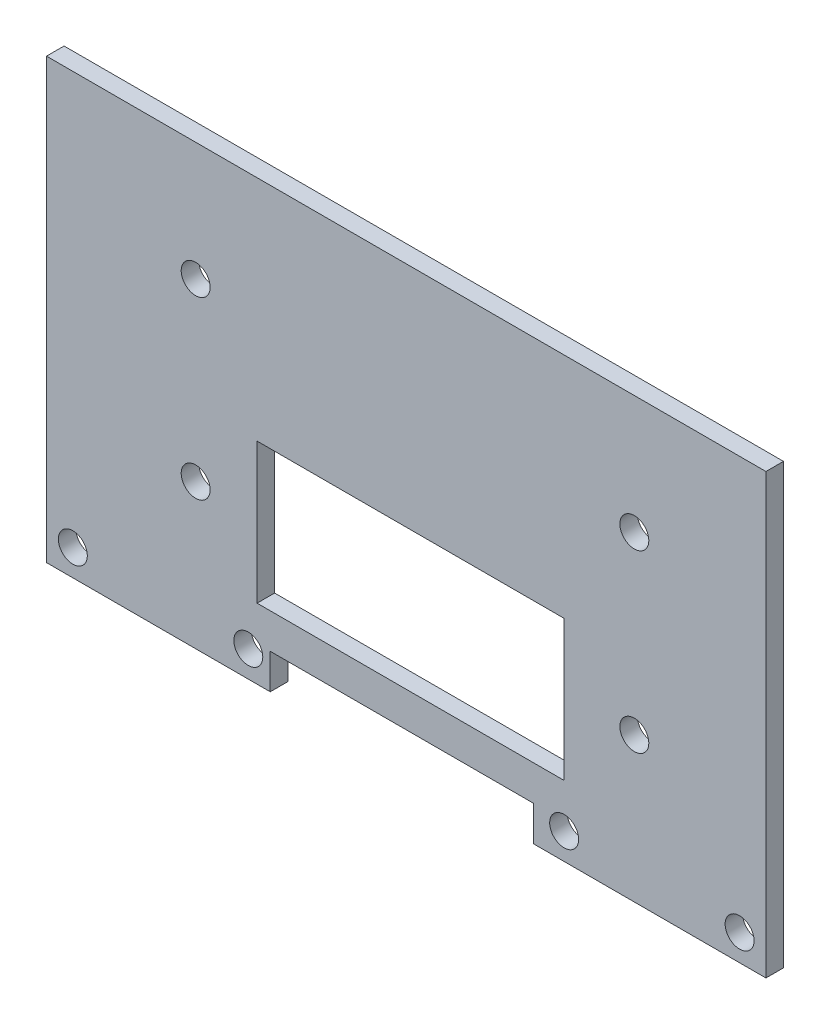
SolidWorks part; units mm, degrees
material "环氧板"
ref_plane "前视基准面" through (0, 0, 0) normal (0, 0, 1) x (1, 0, 0)
ref_plane "上视基准面" through (0, 0, 0) normal (0, 1, 0) x (1, 0, 0)
ref_plane "右视基准面" through (0, 0, 0) normal (1, 0, 0) x (0, 0, -1)
other "Configuration Table"
sketch "草图1" plane through (0, 0, 0) normal (0, 0, 1) x (1, 0, 0)
  line L1 (-40, 25) -> (40, 25)
  line L2 (-40, 25) -> (-40, -25)
  line L3 (-40, -25) -> (40, -25)
  line L4 (40, 25) -> (40, -25)
  line L5 (-40, 25) -> (40, -25) construction
  line L6 (-40, -25) -> (40, 25) construction
  point P0 (0, 0)
  dimension "D1" = 50
  dimension "D2" = 80
extrude "凸台-拉伸1" add sketch "草图1" along normal blind 2
sketch "草图5" plane through (0, 0, 2) normal (0, 0, 1) x (1, 0, 0)
  line L1 (-40, 25) -> (-42, 25)
  line L2 (-40, 25) -> (-40, -25)
  line L3 (-40, -25) -> (-42, -25)
  line L4 (-42, 25) -> (-42, -25)
  dimension "D1" = 2
extrude "凸台-拉伸2" add sketch "草图5" against normal blind 2
sketch "草图2" plane through (0, 0, 2) normal (0, 0, 1) x (1, 0, 0)
  line L0 (-42, -25) -> (40, -25) construction
  line L1 (-15, -25) -> (15, -25)
  line L2 (-15, -25) -> (-15, -21)
  line L3 (-15, -21) -> (15, -21)
  line L4 (15, -25) -> (15, -21)
  line L5 (0, 0) -> (0, -38.8497) construction
  line L7 (-18, -1) -> (17, -1)
  line L8 (-18, -1) -> (-18, -17)
  line L9 (-18, -17) -> (17, -17)
  line L10 (17, -1) -> (17, -17)
  line L11 (-42, 25) -> (-42, -25) construction
  dimension "D1" = 4
  dimension "D2" = 30
  dimension "D3" = 4
  dimension "D4" = 35
  dimension "D5" = 16
  dimension "D6" = 24
extrude "切除-拉伸1" cut sketch "草图2" against normal through all
sketch "草图3" plane through (0, 0, 2) normal (0, 0, 1) x (1, 0, 0)
  line L0 (0, 0) -> (0, -32.8394) construction
  line L1 (-42, -25) -> (-15, -25) construction
  line L4 (-42, 25) -> (-42, -25) construction
  circle A0 centre (-39, -22) radius 1.65
  circle A1 centre (-19, -22) radius 1.65
  circle A2 centre (17, -22) radius 1.65
  circle A3 centre (37, -22) radius 1.65
  dimension "D1" = 3
  dimension "D2" = 3
  dimension "D3" = 3.3
  dimension "D4" = 20
  dimension "D5" = 17
  dimension "D6" = 20
extrude "切除-拉伸2" cut sketch "草图3" against normal through all
sketch "草图4" plane through (0, 0, 2) normal (0, 0, 1) x (1, 0, 0)
  line L0 (0, 0) -> (0, 29.2833) construction
  line L1 (40, 25) -> (-42, 25) construction
  line L3 (20, 20) -> (22.3, 20)
  line L4 (20, 20) -> (20, -5.3)
  line L5 (20, -5.3) -> (22.3, -5.3)
  line L6 (22.3, 20) -> (22.3, -5.3)
  line L10 (-22.3, 20) -> (-22.3, -5.3)
  line L11 (-20, -5.3) -> (-22.3, -5.3)
  line L12 (-20, 20) -> (-20, -5.3)
  line L13 (-20, 20) -> (-22.3, 20)
  dimension "D1" = 2.3
  dimension "D2" = 25.3
  dimension "D3" = 5
  dimension "D4" = 20
extrude "切除-拉伸3" [suppressed] cut sketch "草图4" against normal blind 10
sketch "草图6" plane through (0, 0, 2) normal (0, 0, 1) x (1, 0, 0)
  line L1 (-15, -25) -> (-16.5, -25)
  line L2 (-15, -25) -> (-15, -21)
  line L3 (-15, -21) -> (-16.5, -21)
  line L4 (-16.5, -25) -> (-16.5, -21)
  dimension "D1" = 1.5
extrude "切除-拉伸4" cut sketch "草图6" against normal through all
sketch "草图7" plane through (0, 0, 2) normal (0, 0, 1) x (1, 0, 0)
  line L0 (15, -21) -> (-16.5, -21) construction
  line L1 (15, -25) -> (13.5, -25)
  line L2 (15, -25) -> (15, -21)
  line L3 (15, -21) -> (13.5, -21)
  line L4 (13.5, -25) -> (13.5, -21)
  dimension "D1" = 1.5
extrude "凸台-拉伸3" add sketch "草图7" against normal blind 2
sketch "草图8" plane through (0, 0, 2) normal (0, 0, 1) x (1, 0, 0)
  circle A1 centre (-25, 11.5) radius 1.65
  circle A2 centre (-25, 11.5) radius 1.65
  circle A3 centre (-25, -8.5) radius 1.65
  circle A4 centre (-25, -8.5) radius 1.65
  circle A5 centre (25, -8.5) radius 1.65
  circle A6 centre (25, -8.5) radius 1.65
  circle A7 centre (25, 11.5) radius 1.65
  circle A8 centre (25, 11.5) radius 1.65
  dimension "D1" = 0
  dimension "D2" = 0
  dimension "D3" = 0
  dimension "D4" = 0
extrude "切除-拉伸5" cut sketch "草图8" against normal through all
